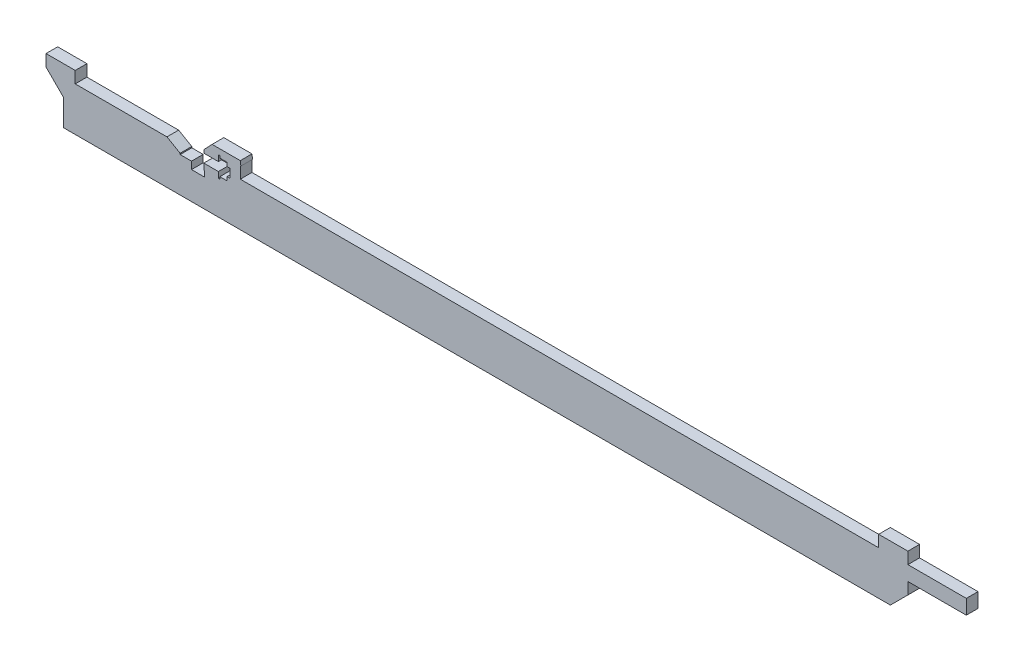
SolidWorks part; units mm, degrees
ref_plane "Front Plane" through (0, 0, 0) normal (0, 0, 1) x (1, 0, 0)
ref_plane "Top Plane" through (0, 0, 0) normal (0, 1, 0) x (1, 0, 0)
ref_plane "Right Plane" through (0, 0, 0) normal (1, 0, 0) x (0, 0, -1)
sketch "Sketch1" plane through (0, 0, 0) normal (0, 0, 1) x (1, 0, 0)
  line L1 (0, 0) -> (20, 0)
  line L2 (-289, -1) -> (-295, 5)
  line L3 (0, 5) -> (20, 5)
  line L4 (20, 0) -> (20, 5)
  line L5 (-10, 5) -> (-228.5, 5)
  line L6 (0, 0) -> (0, -10)
  line L7 (0, -10) -> (-289, -10)
  line L8 (-289, -1) -> (-289, -10)
  line L9 (-249.0932, 5) -> (-285, 5)
  line L10 (-295, 5) -> (-295, 9)
  line L11 (-295, 9) -> (-285, 9)
  line L12 (-285, 5) -> (-285, 9)
  line L13 (-241, 2.5) -> (-240.8, 1.1345)
  line L14 (-240.8, 1.1345) -> (-240.8, -0.5)
  line L15 (-240.8, -0.5) -> (-245.2, -0.5)
  line L16 (-245.2, -0.5) -> (-245.2, 2)
  line L17 (-245.2, 2) -> (-249.0932, 2)
  line L18 (0, 5) -> (0, 9)
  line L19 (0, 9) -> (-10, 9)
  line L20 (-10, 5) -> (-10, 9)
  line L21 (-249.0932, 2) -> (-249.0932, 5)
  line L22 (-245, 0) -> (-241, 0) construction
  line L23 (-245, 0) -> (-245, 10) construction
  line L24 (-241, 0) -> (-241, 10) construction
  line L25 (-245, 10) -> (-241, 10) construction
  line L26 (-245, 0) -> (-241, 10) construction
  line L27 (-261, 30) -> (-209.2068, 30) construction
  line L28 (-261, 30) -> (-261, 10) construction
  line L29 (-240, 30) -> (-240, 10) construction
  line L30 (-261, 10) -> (-240, 10) construction
  line L31 (-261, 30) -> (-240, 10) construction
  line L32 (-240, 30) -> (-261, 10) construction
  line L57 (-241, 0) -> (-245, 10) construction
  line L100 (-243, 5) -> (-228.8671, 5) construction
  line L101 (-241, 6.475) -> (-241, 7.5)
  line L102 (-233, 3.525) -> (-232, 3.525)
  line L103 (-233, 2.25) -> (-233, 3.525)
  line L104 (-241, 7.5) -> (-238.1429, 10.5)
  line L105 (-238.1429, 10.5) -> (-228.5, 10.5)
  line L106 (-228.5, 10.5) -> (-228.3, 9)
  line L107 (-228.3, 9) -> (-228.5, 9)
  line L108 (-228.5, 9) -> (-228.5, 5)
  line L109 (-241, 6.475) -> (-236, 6.475)
  line L110 (-236, 6.475) -> (-236, 8.5)
  line L111 (-236, 8.5) -> (-235.5, 8.5)
  line L112 (-235.5, 8.5) -> (-235.5, 7.75)
  line L113 (-235.5, 7.75) -> (-233, 7.75)
  line L114 (-233, 7.75) -> (-233, 6.475)
  line L115 (-233, 6.475) -> (-232, 6.475)
  line L116 (-232, 6.475) -> (-232, 3.525)
  line L117 (-235.5, 2.25) -> (-233, 2.25)
  line L118 (-235.5, 1.5) -> (-235.5, 2.25)
  line L119 (-236, 1.5) -> (-235.5, 1.5)
  line L120 (-236, 3.525) -> (-236, 1.5)
  line L121 (-241, 3.525) -> (-236, 3.525)
  line L122 (-241, 3.525) -> (-241, 2.5)
  point P27 (-243, 5)
  point P130 (-232, 5)
  dimension "D21" = 0.5
  dimension "D24" = 5
  dimension "D1" = 289
  dimension "D2" = 20
  dimension "D3" = 5
  dimension "D4" = 4
  dimension "D5" = 10
  dimension "D6" = 1
  dimension "D7" = 10
  dimension "D8" = 6
  dimension "D9" = 6
  dimension "D10" = 6
  dimension "D11" = 4
  dimension "D12" = 0.2
  dimension "D13" = 11.5
  dimension "D14" = 10
  dimension "D15" = 4
  dimension "D16" = 2.95
  dimension "D17" = 7
  dimension "D18" = 20
  dimension "D19" = 49
  dimension "D20" = 25
  dimension "D22" = 0.2
  dimension "D23" = 0.2
  dimension "D25" = 1.5
  dimension "D35" = 5.5
  dimension "D39" = 0.5
  dimension "D40" = 2.5
  dimension "D41" = 1
  dimension "D43" = 8
  dimension "D44" = 1
  dimension "D45" = 1
extrude "Boss-Extrude1" add sketch "Sketch1" along normal blind 4
chamfer "Chamfer1" distance 6 angle 45 1 edges at (0, -10, 2)
chamfer "Chamfer2" distance 2.6 angle 60 1 edges at (-249.0932, 5, 2)
sketch "Sketch2" plane through (-232, 0, 0) normal (-1, 0, 0) x (0, 0, 1)
  line L0 (4, 5) -> (2, 5) construction
  line L1 (4, 6.475) -> (4, 3.525) construction
  line L2 (2, 6.475) -> (2, 5) construction
  line L3 (4, 6.475) -> (0, 6.475) construction
  circle A0 centre (2, 5) radius 0.4645
extrude "Cut-Extrude1" cut sketch "Sketch2" against normal blind 0.5
